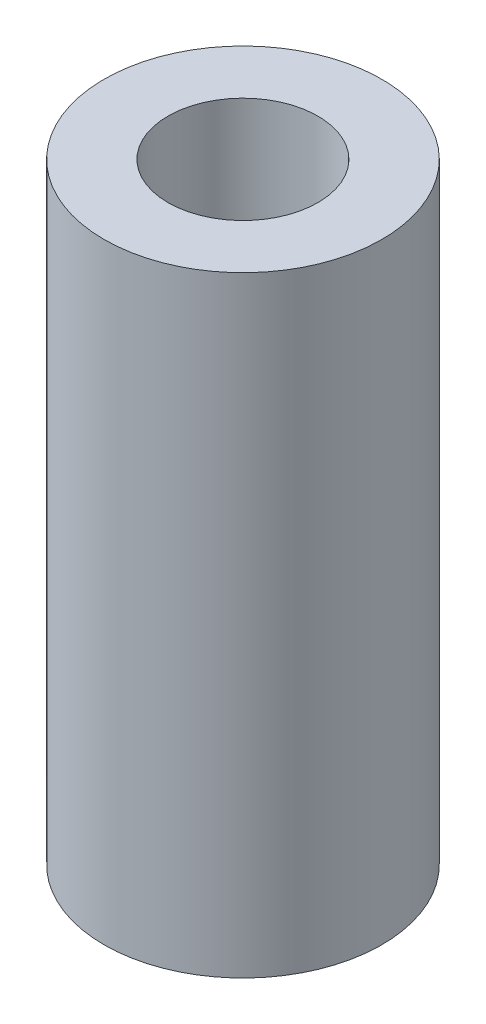
SolidWorks part; units mm, degrees
ref_plane "Спереди" through (0, 0, 0) normal (0, 0, 1) x (1, 0, 0)
ref_plane "Сверху" through (0, 0, 0) normal (0, 1, 0) x (1, 0, 0)
ref_plane "Справа" through (0, 0, 0) normal (1, 0, 0) x (0, 0, -1)
sketch "Эскиз1" plane through (0, 0, 0) normal (0, 1, 0) x (1, 0, 0)
  circle A0 centre (0, 0) radius 2.5
  circle A1 centre (0, 0) radius 1.35
  dimension "D1" = 5
  dimension "D2" = 2.7
extrude "Бобышка-Вытянуть1" add sketch "Эскиз1" along normal blind 11
